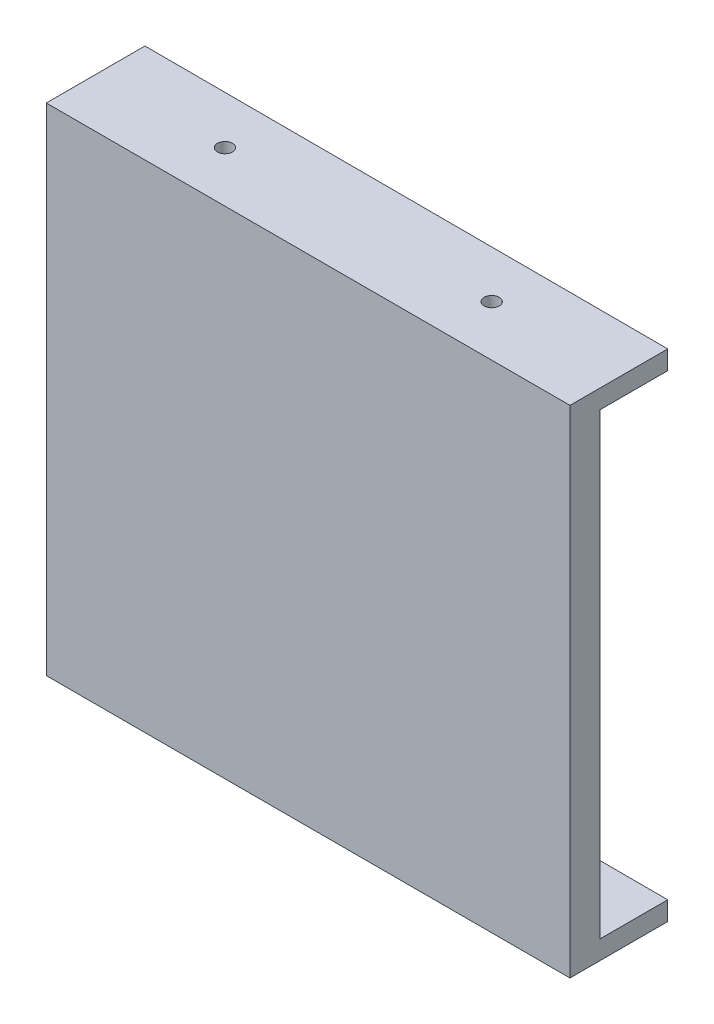
SolidWorks part; units mm, degrees
ref_plane "Front Plane" through (0, 0, 0) normal (0, 0, 1) x (1, 0, 0)
ref_plane "Top Plane" through (0, 0, 0) normal (0, 1, 0) x (1, 0, 0)
ref_plane "Right Plane" through (0, 0, 0) normal (1, 0, 0) x (0, 0, -1)
sketch "Sketch1" plane through (0, 0, 0) normal (0, 0, 1) x (1, 0, 0)
  line L1 (52.3259, 0) -> (191.1688, 0)
  line L2 (52.3259, 0) -> (52.3259, -131.4752)
  line L3 (52.3259, -131.4752) -> (191.1688, -131.4752)
  line L4 (191.1688, 0) -> (191.1688, -131.4752)
extrude "Boss-Extrude1" add sketch "Sketch1" against normal blind 8
sketch "Sketch3" plane through (0, 0, 0) normal (0, 0, 1) x (1, 0, 0)
  line L0 (191.1688, -131.4752) -> (191.1688, 0) construction
  line L1 (52.3259, 0) -> (191.1688, 0)
  line L2 (52.3259, 0) -> (52.3259, -5)
  line L3 (52.3259, -5) -> (191.1688, -5)
  line L4 (191.1688, 0) -> (191.1688, -5)
  line L6 (52.3259, -131.4752) -> (191.1688, -131.4752)
  line L7 (52.3259, -131.4752) -> (52.3259, -126.4752)
  line L8 (52.3259, -126.4752) -> (191.1688, -126.4752)
  line L9 (191.1688, -131.4752) -> (191.1688, -126.4752)
  dimension "D1" = 5
  dimension "D2" = 5
extrude "Boss-Extrude2" add sketch "Sketch3" against normal up to surface (25.913 mm away)
sketch "Sketch4" plane through (0, -131.4752, 0) normal (0, -1, 0) x (1, 0, 0)
  line L0 (135.6127, -26.013) -> (128.6989, -14.0379)
  line L1 (191.1688, -25.913) -> (52.3259, -26.163) construction
  line L2 (128.6989, -14.0379) -> (135.6127, -26.013) construction
  line L3 (128.6989, -14.0379) -> (114.8425, -14.0379)
  line L4 (114.8425, -14.0379) -> (108.0155, -26.0627)
  line L5 (108.0155, -26.0627) -> (135.6127, -26.013)
extrude "Cut-Extrude1" cut sketch "Sketch4" against normal up to next
sketch "Sketch5" plane through (0, -131.4752, 0) normal (0, -1, 0) x (1, 0, 0)
  circle A0 centre (86.267, -13.435) radius 2
  circle A1 centre (156.9777, -13.435) radius 2
  dimension "D1" = 4
  dimension "D2" = 4
extrude "Cut-Extrude2" cut sketch "Sketch5" against normal through all
